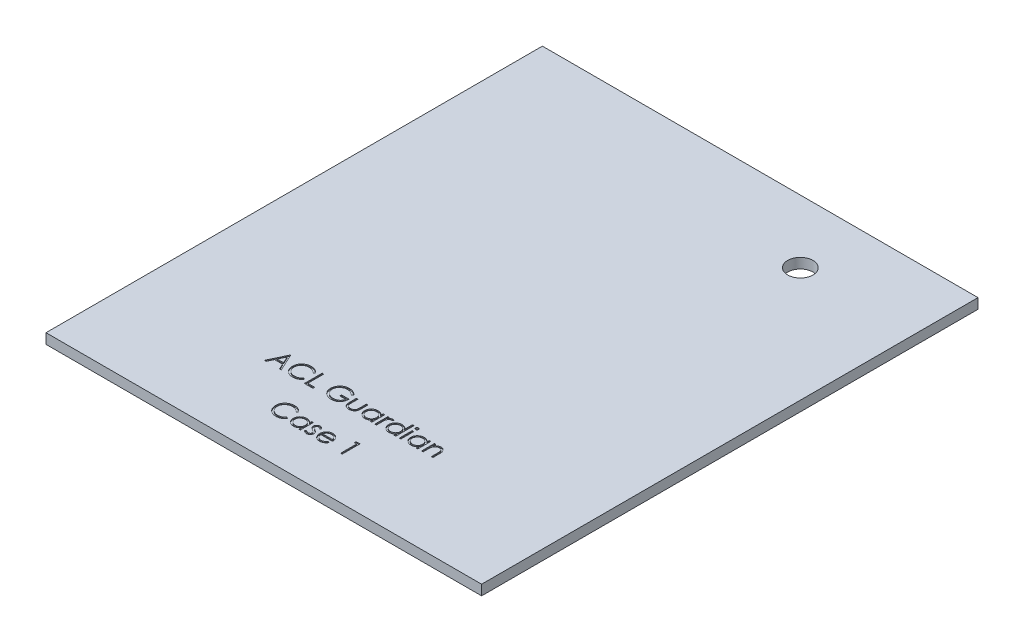
SolidWorks part; units mm, degrees
ref_plane "Front Plane" through (0, 0, 0) normal (0, 0, 1) x (1, 0, 0)
ref_plane "Top Plane" through (0, 0, 0) normal (0, 1, 0) x (1, 0, 0)
ref_plane "Right Plane" through (0, 0, 0) normal (1, 0, 0) x (0, 0, -1)
sketch "Sketch1" plane through (0, 0, 0) normal (0, 0, 1) x (1, 0, 0)
  line L1 (0, 0) -> (86, 0)
  line L2 (0, 0) -> (0, -2)
  line L3 (0, -2) -> (86, -2)
  line L4 (86, 0) -> (86, -2)
  dimension "D1" = 2
  dimension "D2" = 86
extrude "Boss-Extrude1" add sketch "Sketch1" along normal blind 98
sketch "Sketch2" plane through (0, 0, 0) normal (0, 1, 0) x (1, 0, 0)
  line L0 (43, 0) -> (43, -98) construction
  line L1 (86, 0) -> (0, 0) construction
  line L2 (86, -98) -> (0, -98) construction
  line L3 (0, -12.4218) -> (86, -12.4218) construction
  line L4 (0, -98) -> (0, 0) construction
  line L5 (86, -98) -> (86, 0) construction
  circle A1 centre (63.3463, -12.4218) radius 2.5
  dimension "D1" = 5
extrude "Cut-Extrude1" cut sketch "Sketch2" against normal blind 98
sketch "Sketch3" plane through (0, 0, 0) normal (0, 1, 0) x (1, 0, 0)
  line L0 (0, -81.1608) -> (86, -81.1608) construction
  line L1 (0, -98) -> (0, 0) construction
  line L2 (86, -98) -> (86, 0) construction
  line L3 (0, -89.5108) -> (86, -89.5108) construction
  text T0 "ACL Guardian"
  text T1 "Case 1"
extrude "Cut-Extrude2" cut sketch "Sketch3" against normal blind 0.2
